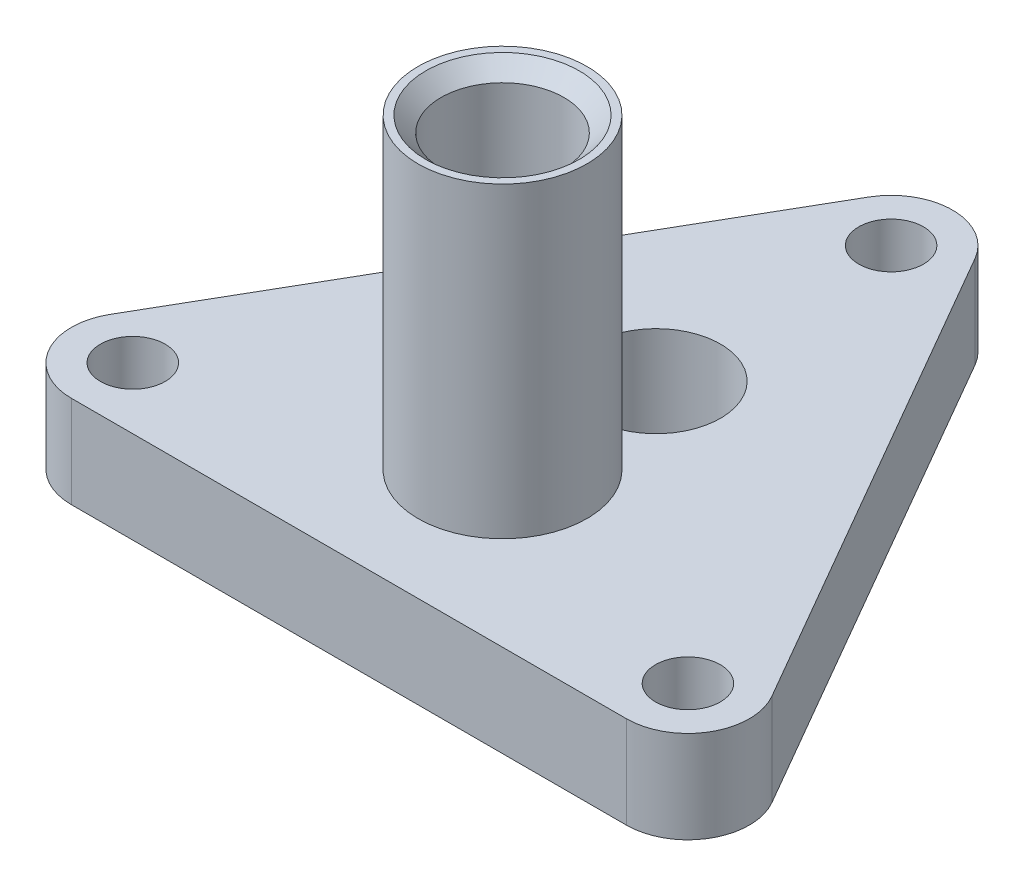
SolidWorks part; units mm, degrees
ref_plane "Front Plane" through (0, 0, 0) normal (0, 0, 1) x (1, 0, 0)
ref_plane "Top Plane" through (0, 0, 0) normal (0, 1, 0) x (1, 0, 0)
ref_plane "Right Plane" through (0, 0, 0) normal (1, 0, 0) x (0, 0, -1)
sketch "Sketch1" plane through (0, 0, 0) normal (0, 1, 0) x (1, 0, 0)
  line L0 (0, 0) -> (9.0359, 0)
  line L1 (10.7679, 3) -> (1.7321, 18.6506)
  line L2 (-1.7321, 18.6506) -> (-10.7679, 3)
  line L3 (-9.0359, 0) -> (0, 0)
  arc A0 (9.0359, 0) -> (10.7679, 3) centre (9.0359, 2) ccw
  arc A1 (-10.7679, 3) -> (-9.0359, 0) centre (-9.0359, 2) ccw
  arc A2 (1.7321, 18.6506) -> (-1.7321, 18.6506) centre (0, 17.6506) ccw
  circle A3 centre (0, 17.6506) radius 1.054
  circle A4 centre (-9.0359, 2) radius 1.054
  circle A5 centre (9.0359, 2) radius 1.054
  point P7 (12.5, 0)
  point P10 (-12.5, 0)
  point P13 (0, 21.6506)
  dimension "D5" = 2
  dimension "D1" = 60
  dimension "D2" = 60
  dimension "D3" = 25
  dimension "D4" = 12.5
extrude "Boss-Extrude1" add sketch "Sketch1" along normal blind 3
sketch "Sketch2" plane through (0, 3, 0) normal (0, 1, 0) x (1, 0, 0)
  line L0 (-9.0359, 0) -> (9.0359, 0) construction
  circle A0 centre (0, 5) radius 0.8
  circle A1 centre (0, 10) radius 2.0955
  dimension "D1" = 5
  dimension "D2" = 10
extrude "Cut-Extrude1" cut sketch "Sketch2" against normal through all
sketch "Sketch3" plane through (0, 3, 0) normal (0, 1, 0) x (1, 0, 0)
  circle A1 centre (0, 5) radius 2.75
extrude "Boss-Extrude2" add sketch "Sketch3" along normal blind 10
sketch "Sketch4" plane through (0, 3, 0) normal (0, 1, 0) x (1, 0, 0)
  circle A0 centre (0, 5) radius 2
extrude "Cut-Extrude2" cut sketch "Sketch4" along normal up to next
chamfer "Chamfer1" distance 2 angle 20 1 edges at (0, 3, -3)
chamfer "Chamfer2" distance 0.5 angle 45 1 edges at (0, 13, -3)
